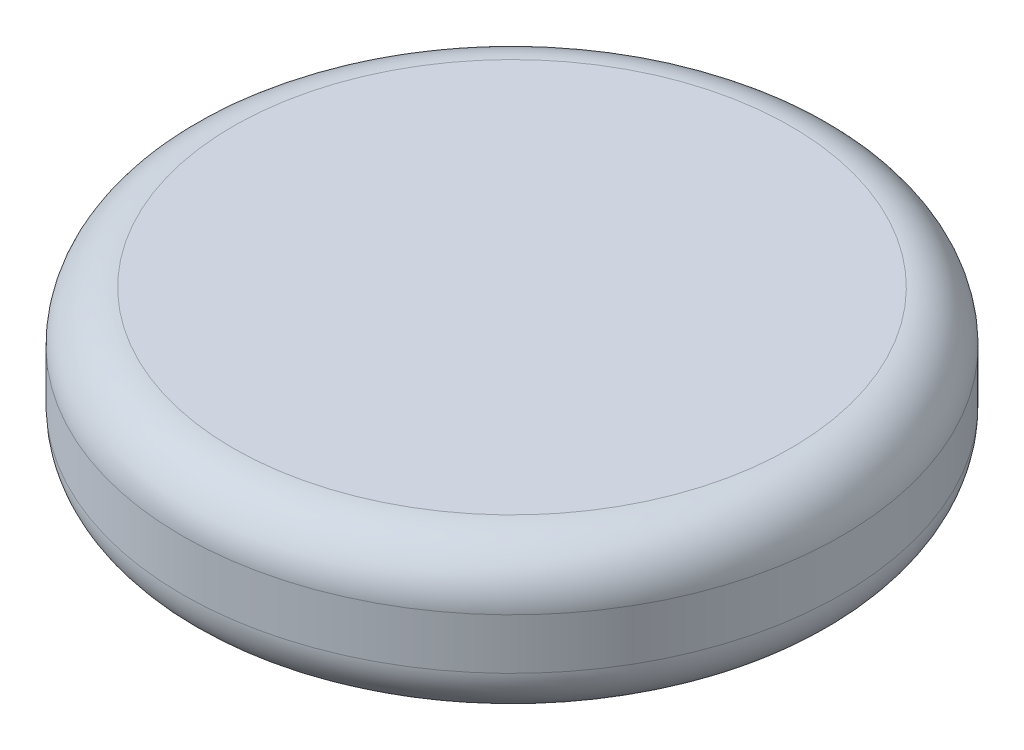
SolidWorks part; units mm, degrees
ref_plane "Front Plane" through (0, 0, 0) normal (0, 0, 1) x (1, 0, 0)
ref_plane "Top Plane" through (0, 0, 0) normal (0, 1, 0) x (1, 0, 0)
ref_plane "Right Plane" through (0, 0, 0) normal (1, 0, 0) x (0, 0, -1)
sketch "Sketch1" plane through (0, 0, 0) normal (0, 1, 0) x (1, 0, 0)
  circle A0 centre (0, 0) radius 41.275
  dimension "D1" = 82.55
extrude "Boss-Extrude1" add sketch "Sketch1" along normal blind 19.05
fillet "Fillet1" radius 6.35 2 edges at (0, 0, 41.275) (0, 19.05, 41.275)
